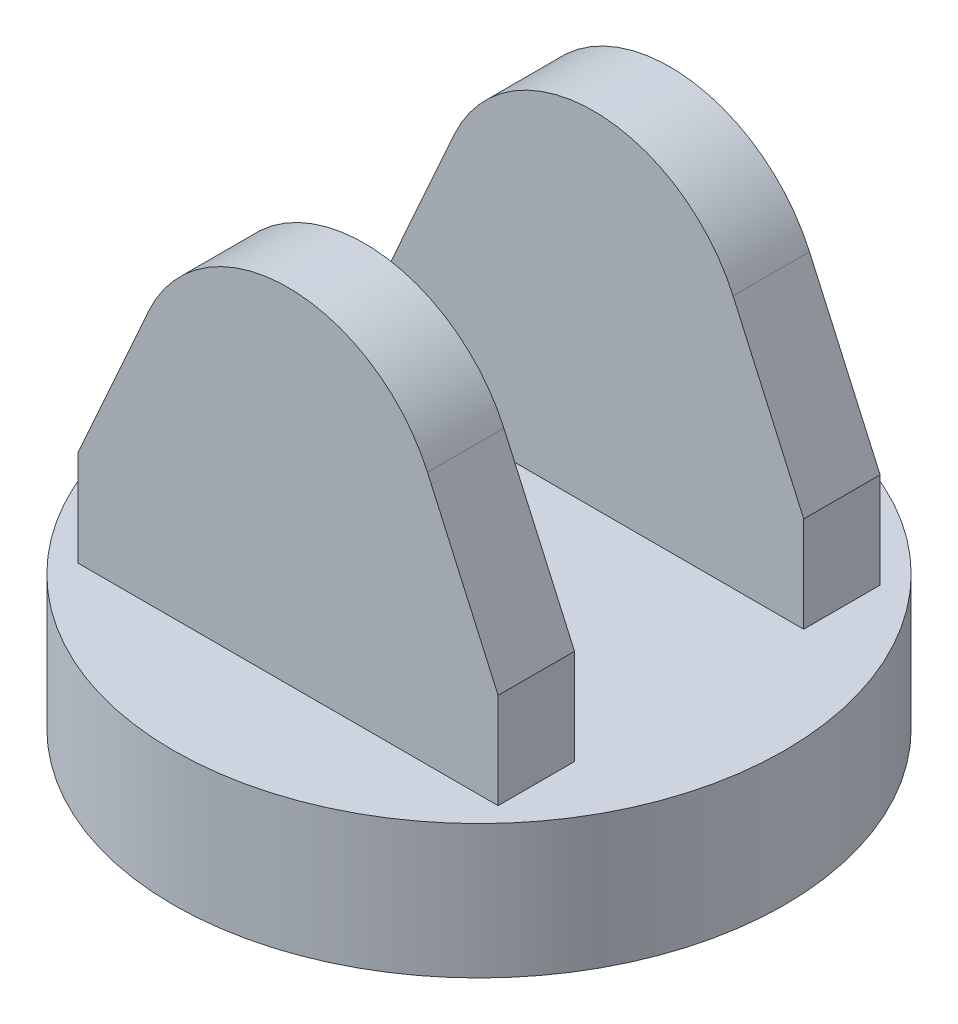
SolidWorks part; units mm, degrees
ref_plane "Alzado" through (0, 0, 0) normal (0, 0, 1) x (1, 0, 0)
ref_plane "Planta" through (0, 0, 0) normal (0, 1, 0) x (1, 0, 0)
ref_plane "Vista lateral" through (0, 0, 0) normal (1, 0, 0) x (0, 0, -1)
sketch "Croquis1" plane through (0, 0, 0) normal (0, 1, 0) x (1, 0, 0)
  line L1 (-25, -57.5) -> (25, -57.5)
  line L2 (-25, -57.5) -> (-25, 57.5)
  line L3 (-25, 57.5) -> (25, 57.5)
  line L4 (25, -57.5) -> (25, 57.5)
  line L5 (-25, -57.5) -> (25, 57.5) construction
  line L6 (-25, 57.5) -> (25, -57.5) construction
  line L7 (-25, 25) -> (-40, 25)
  line L8 (-25, 25) -> (-25, -25)
  line L9 (-25, -25) -> (-40, -25)
  line L10 (-40, 25) -> (-40, -25)
  point P0 (0, 0)
  point P10 (-40, 0)
  dimension "D1" = 50
  dimension "D2" = 115
  dimension "D3" = 50
  dimension "D4" = 15
extrude "Saliente-Extruir1" add sketch "Croquis1" along normal blind 250 contours L7 L10 L9 L2 | L1 L4 L3 L2
sketch "Croquis2" plane through (0, 250, 0) normal (0, 1, 0) x (1, 0, 0)
  line L0 (-25, 25) -> (-25, -25) construction
  circle A0 centre (-25, 0) radius 80
  dimension "D1" = 160
extrude "Saliente-Extruir2" add sketch "Croquis2" along normal blind 35
sketch "Croquis3" plane through (0, 0, 0) normal (0, 0, 1) x (1, 0, 0)
  line L0 (-25, 285) -> (-25, 375) construction
  line L1 (55, 285) -> (-105, 285) construction
  line L2 (11.5142, 351.3313) -> (30, 310)
  line L3 (30, 310) -> (30, 285)
  line L4 (30, 285) -> (-80, 285)
  line L5 (-80, 310) -> (-80, 285)
  line L6 (-61.5142, 351.3313) -> (-80, 310)
  arc A0 (-61.5142, 351.3313) -> (11.5142, 351.3313) centre (-25, 335) cw
  dimension "D4" = 40
  dimension "D1" = 110
  dimension "D2" = 25
  dimension "D3" = 50
extrude "Saliente-Extruir3" add sketch "Croquis3" along normal mid plane 100
sketch "Croquis4" plane through (30, 0, 0) normal (1, 0, 0) x (0, 0, -1)
  line L0 (50, 375) -> (-50, 375) construction
  line L1 (-30, 375) -> (30, 375)
  line L2 (-30, 375) -> (-30, 285)
  line L3 (-30, 285) -> (30, 285)
  line L4 (30, 375) -> (30, 285)
  line L5 (-50, 285) -> (50, 285) construction
  point P8 (0, 375)
  point P10 (0, 285)
  dimension "D1" = 60
extrude "Cortar-Extruir1" cut sketch "Croquis4" against normal through all
sketch "Croquis5" plane through (0, 250, 0) normal (0, -1, 0) x (1, 0, 0)
  circle A1 centre (-25, 0) radius 80
  circle A2 centre (-25, 0) radius 80
  dimension "D1" = 0
extrude "Cortar-Extruir2" cut sketch "Croquis5" along normal through all
